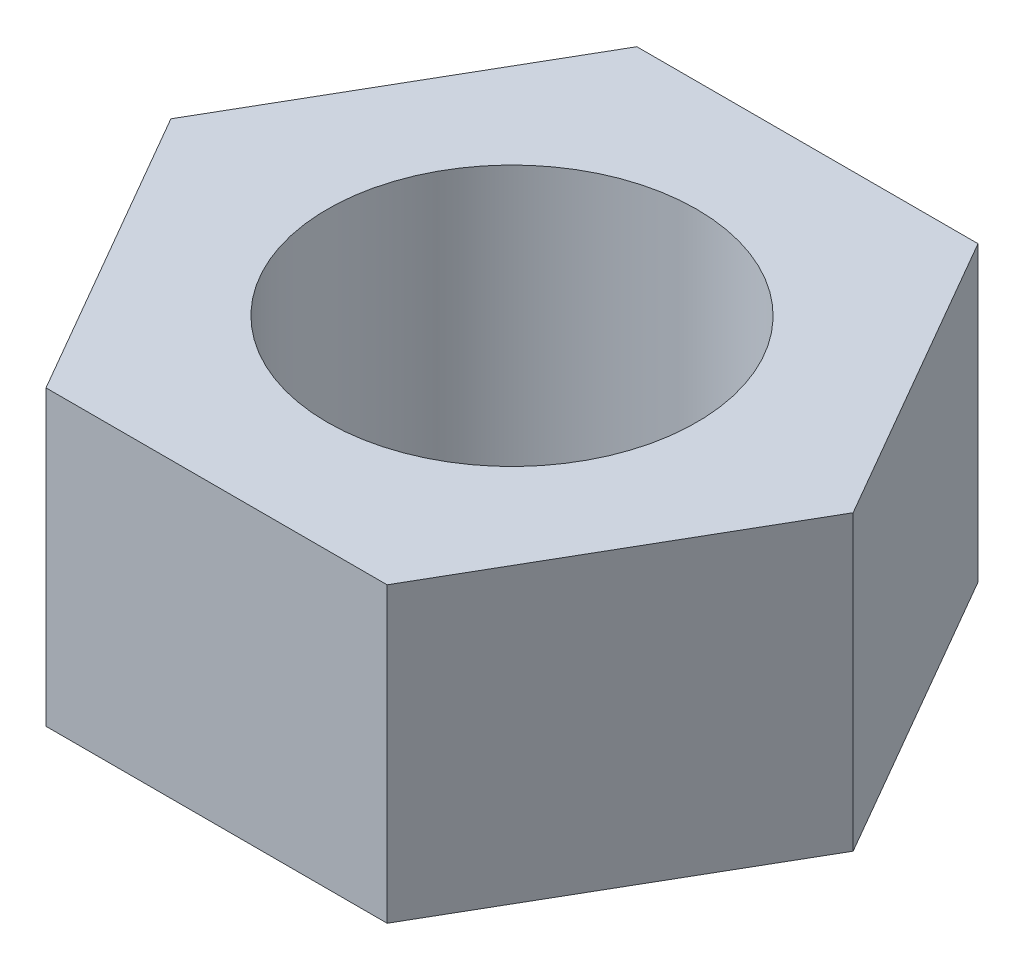
SolidWorks part; units mm, degrees
ref_plane "Plan de face" through (0, 0, 0) normal (0, 0, 1) x (1, 0, 0)
ref_plane "Plan de dessus" through (0, 0, 0) normal (0, 1, 0) x (1, 0, 0)
ref_plane "Plan de droite" through (0, 0, 0) normal (1, 0, 0) x (0, 0, -1)
sketch "Esquisse1" plane through (0, 0, 0) normal (0, 1, 0) x (1, 0, 0)
  line L1 (7.3901, 0) -> (3.695, 6.4)
  line L2 (3.695, 6.4) -> (-3.695, 6.4)
  line L3 (-3.695, 6.4) -> (-7.3901, 0)
  line L4 (-7.3901, 0) -> (-3.695, -6.4)
  line L5 (-3.695, -6.4) -> (3.695, -6.4)
  line L6 (3.695, -6.4) -> (7.3901, 0)
  circle A0 centre (0, 0) radius 6.4 construction
  circle A1 centre (0, 0) radius 4
  dimension "D1" = 12.8
  dimension "D2" = 8
extrude "Boss.-Extru.1" add sketch "Esquisse1" along normal blind 6.35
